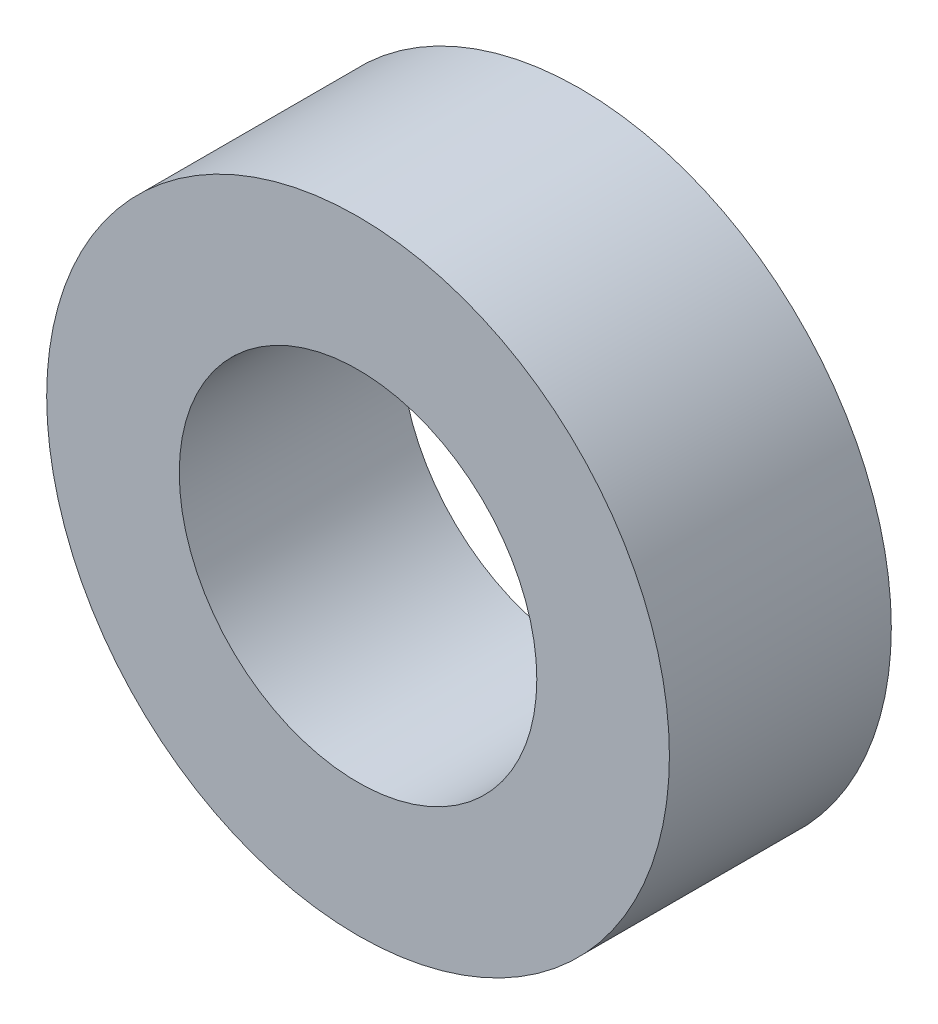
SolidWorks part; units mm, degrees
material "6061 Alloy"
ref_plane "Front Plane" through (0, 0, 0) normal (0, 0, 1) x (1, 0, 0)
ref_plane "Top Plane" through (0, 0, 0) normal (0, 1, 0) x (1, 0, 0)
ref_plane "Right Plane" through (0, 0, 0) normal (1, 0, 0) x (0, 0, -1)
sketch "Sketch2" plane through (0, 0, 0) normal (0, 0, 1) x (1, 0, 0)
  circle A0 centre (0, 0) radius 11.4046
  circle A1 centre (0, 0) radius 6.5481
  dimension "D1" = 13.0962
  dimension "D2" = 22.8092
extrude "Boss-Extrude1" add sketch "Sketch2" along normal blind 8.128
